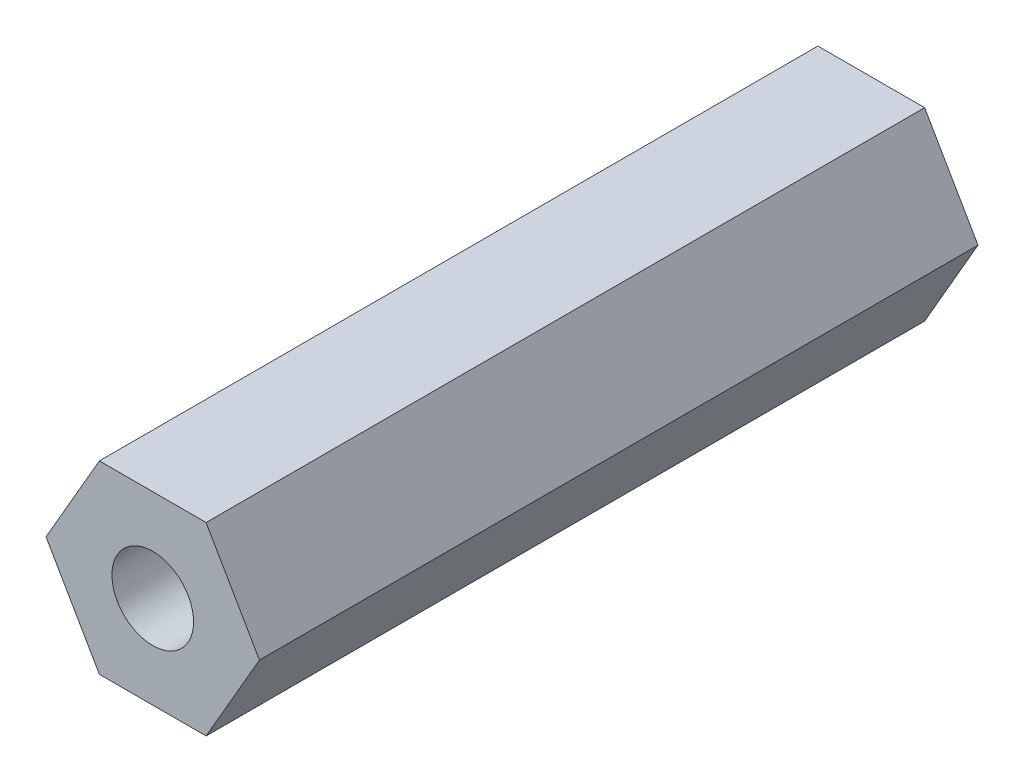
SolidWorks part; units mm, degrees
material "AISI 304"
ref_plane "前视基准面" through (0, 0, 0) normal (0, 0, 1) x (1, 0, 0)
ref_plane "上视基准面" through (0, 0, 0) normal (0, 1, 0) x (1, 0, 0)
ref_plane "右视基准面" through (0, 0, 0) normal (1, 0, 0) x (0, 0, -1)
sketch "草图1" plane through (0, 0, 0) normal (0, 0, 1) x (1, 0, 0)
  line L1 (1.6339, 2.83) -> (-1.6339, 2.83)
  line L2 (-1.6339, 2.83) -> (-3.2678, 0)
  line L3 (-3.2678, 0) -> (-1.6339, -2.83)
  line L4 (-1.6339, -2.83) -> (1.6339, -2.83)
  line L5 (1.6339, -2.83) -> (3.2678, 0)
  line L6 (3.2678, 0) -> (1.6339, 2.83)
  circle A0 centre (0, 0) radius 2.83 construction
  dimension "六角对边长度" = 5.66
extrude "六角柱长度" add sketch "草图1" along normal mid plane 22
hole_wizard "螺纹孔1" positions "草图2" profile "草图3" tap size "M2" standard "GB"
sketch "草图2" plane through (0, 0, 11) normal (0, 0, 1) x (1, 0, 0)
  point P0 (0, 0)
cosmetic thread "孔螺蚊线1" parameters "D1"=12, "D2"=3
sketch "草图3" plane through (0, 0, 11) normal (1, 0, 0) x (0, -1, 0)
  line L0 (0, 0) -> (0, 13.9511)
  line L1 (0, 13.9511) -> (1.25, 13.2)
  line L2 (1.25, 13.2) -> (1.25, 0)
  line L5 (1.25, 0) -> (0, 0)
  line L10 (0, 13.9511) -> (-1.25, 13.2) construction
  line L11 (0, -6.35) -> (0, 107.95) construction
  dimension "螺纹孔钻头直径" = 2.5
  dimension "螺纹孔钻头深度" = 13.2
  dimension "导头角度" = 118
mirror "镜向1" about plane through (0, 0, 0) normal (0, 0, 1) of "螺纹孔1"
cosmetic thread "孔螺蚊线2" parameters "D1"=12, "D2"=3
